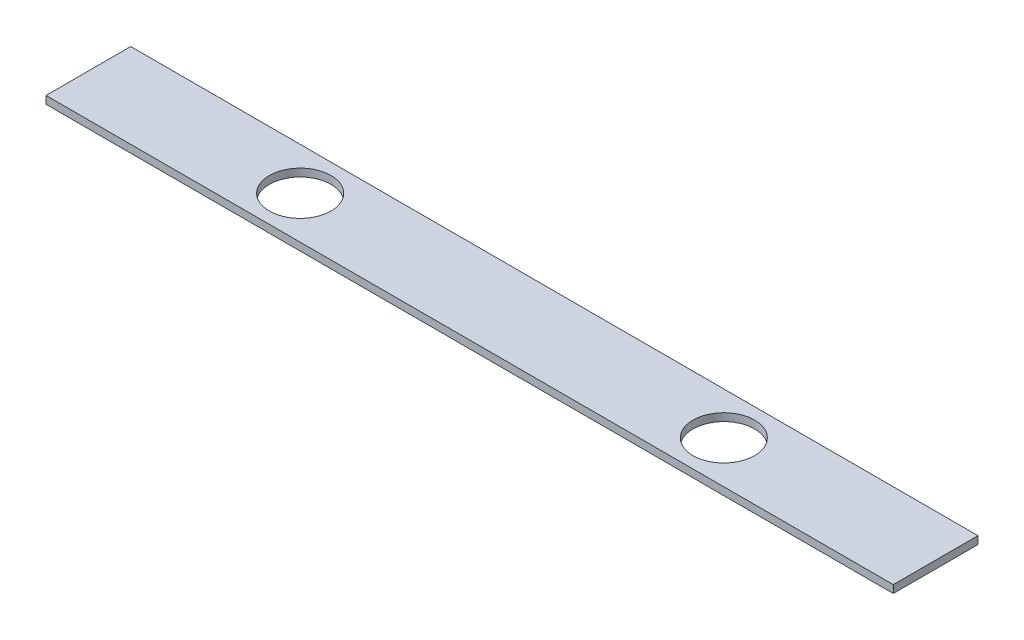
SolidWorks part; units mm, degrees
ref_plane "Płaszczyzna przednia" through (0, 0, 0) normal (0, 0, 1) x (1, 0, 0)
ref_plane "Płaszczyzna górna" through (0, 0, 0) normal (0, 1, 0) x (1, 0, 0)
ref_plane "Płaszczyzna prawa" through (0, 0, 0) normal (1, 0, 0) x (0, 0, -1)
sketch "Szkic1" plane through (0, 0, 0) normal (0, 1, 0) x (1, 0, 0)
  line L1 (0, 0) -> (220, 0)
  line L2 (0, 0) -> (0, 22)
  line L3 (0, 22) -> (220, 22)
  line L4 (220, 0) -> (220, 22)
  circle A0 centre (165, 11) radius 8
  circle A1 centre (55, 11) radius 8
  point P9 (0, 0)
  point P10 (0, 11)
  point P11 (0, 0)
  dimension "D3" = 16
  dimension "D4" = 16
  dimension "D1" = 22
  dimension "D2" = 220
  dimension "D5" = 110
  dimension "D6" = 55
extrude "Dodanie-wyciągnięcie1" add sketch "Szkic1" along normal blind 2
